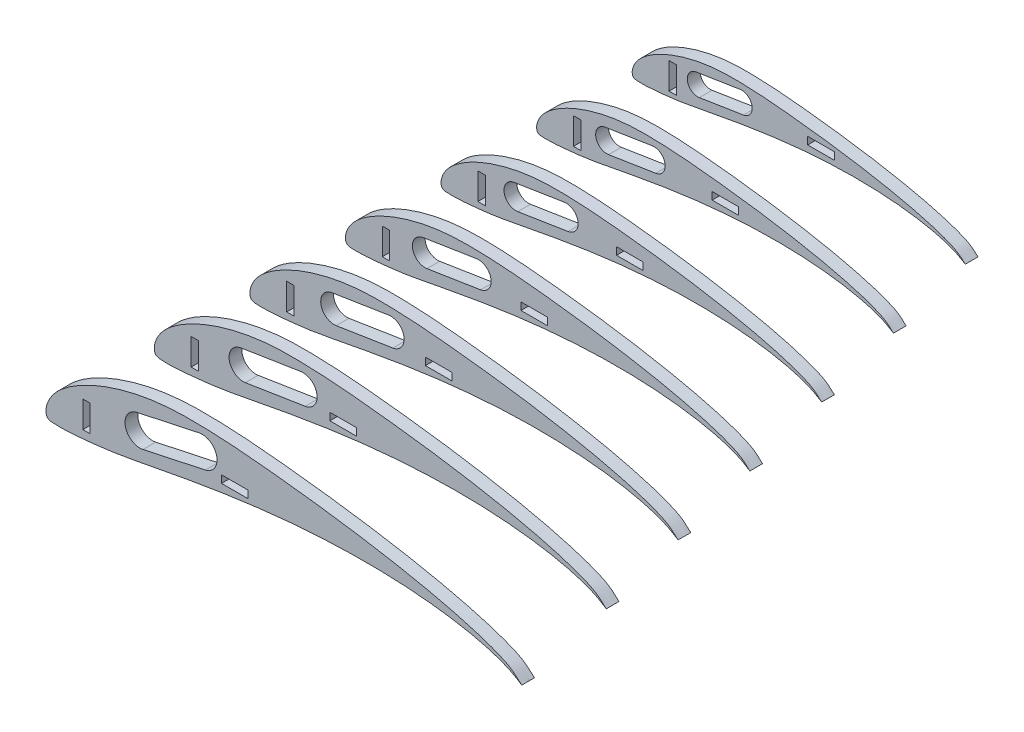
SolidWorks part; units mm, degrees
material "Balsa"
ref_plane "Front Plane" through (0, 0, 0) normal (1, 0, 0) x (0, 1, 0)
ref_plane "Top Plane" through (0, 0, 0) normal (0, 0, 1) x (0, 1, 0)
ref_plane "Right Plane" through (0, 0, 0) normal (0, 1, 0) x (-1, 0, 0)
curve "Curve1"
  spline degree 3 poles (0.9961, 0.0026, 0) (1.0009, -0.0006, 0) (0.9967, 0.0025, 0) (0.9939, 0.0052, 0) (0.9878, 0.0109, 0) (0.9805, 0.017, 0) (0.9705, 0.0231, 0) (0.9581, 0.029, 0) (0.9432, 0.0352, 0) (0.9257, 0.0415, 0) (0.9057, 0.048, 0) (0.8834, 0.0546, 0) (0.8588, 0.0611, 0) (0.8322, 0.0677, 0) (0.8036, 0.0742, 0) (0.7732, 0.0806, 0) (0.7412, 0.0869, 0) (0.7079, 0.0929, 0) (0.6733, 0.0987, 0) (0.6378, 0.1042, 0) (0.6014, 0.1094, 0) (0.5646, 0.1143, 0) (0.5275, 0.1189, 0) (0.4904, 0.1231, 0) (0.4536, 0.1269, 0) (0.4175, 0.1302, 0) (0.3823, 0.1328, 0) (0.3482, 0.1346, 0) (0.3154, 0.1354, 0) (0.284, 0.1353, 0) (0.2541, 0.1338, 0) (0.2258, 0.1307, 0) (0.1988, 0.1263, 0) (0.1732, 0.1206, 0) (0.1489, 0.1139, 0) (0.1262, 0.1063, 0) (0.1051, 0.0981, 0) (0.0858, 0.0892, 0) (0.0682, 0.0798, 0) (0.0525, 0.0701, 0) (0.0388, 0.0602, 0) (0.0271, 0.0502, 0) (0.0176, 0.0401, 0) (0.0103, 0.03, 0) (0.0049, 0.0202, 0) (0.0014, 0.0108, 0) (-0.0002, 0.0022, 0) (0.0001, -0.0051, 0) (0.002, -0.0118, 0) (0.0089, -0.0151, 0) (0.0183, -0.0156, 0) (0.0312, -0.016, 0) (0.0473, -0.0153, 0) (0.0666, -0.0141, 0) (0.0888, -0.012, 0) (0.1137, -0.0092, 0) (0.1411, -0.0057, 0) (0.1711, -0.0007, 0) (0.2038, 0.0055, 0) (0.2393, 0.0123, 0) (0.2775, 0.0195, 0) (0.3182, 0.0267, 0) (0.361, 0.0338, 0) (0.4056, 0.0404, 0) (0.4517, 0.0464, 0) (0.4987, 0.0515, 0) (0.5464, 0.0555, 0) (0.5941, 0.0584, 0) (0.6414, 0.06, 0) (0.6878, 0.0602, 0) (0.7328, 0.059, 0) (0.7758, 0.0564, 0) (0.8164, 0.0525, 0) (0.854, 0.0475, 0) (0.8881, 0.0414, 0) (0.9184, 0.0345, 0) (0.9444, 0.027, 0) (0.9656, 0.0191, 0) (0.9807, 0.0119, 0) (0.9918, 0.0052, 0) (0.9961, 0.0026, 0) (1.0009, -0.0006, 0) (0.9967, 0.0025, 0) knots -0.009748 -0.004147 -0.001 0 0.00098 0.003649 0.007483 0.012095 0.017526 0.024052 0.031783 0.040678 0.05071 0.061833 0.073989 0.087118 0.101145 0.115991 0.13157 0.147788 0.164551 0.181758 0.199312 0.217095 0.23499 0.252857 0.270541 0.287887 0.304773 0.321101 0.336806 0.3518 0.366031 0.379616 0.392653 0.40517 0.417172 0.428604 0.439419 0.449597 0.459102 0.467908 0.475988 0.483309 0.489875 0.495803 0.501149 0.505903 0.510047 0.513579 0.516447 0.51935 0.523823 0.529974 0.537716 0.546968 0.557637 0.56962 0.582804 0.597247 0.613135 0.630444 0.649056 0.668822 0.689595 0.71119 0.733427 0.756094 0.778989 0.80189 0.824567 0.846792 0.868338 0.888978 0.908492 0.926659 0.943286 0.958169 0.971136 0.981956 0.990252 0.995853 0.999 1 1.00098 1.003649 1.007483 periodic
sketch "Sketch2" plane through (0, 0, 0) normal (0, 0, 1) x (0, 1, 0)
  spline S0 degree 3 poles (0.0026, -0.9961) (-0.0006, -1.0009) (0.0025, -0.9967) (0.0052, -0.9939) (0.0109, -0.9878) (0.017, -0.9805) (0.0231, -0.9705) (0.029, -0.9581) (0.0352, -0.9432) (0.0415, -0.9257) (0.048, -0.9057) (0.0546, -0.8834) (0.0611, -0.8588) (0.0677, -0.8322) (0.0742, -0.8036) (0.0806, -0.7732) (0.0869, -0.7412) (0.0929, -0.7079) (0.0987, -0.6733) (0.1042, -0.6378) (0.1094, -0.6014) (0.1143, -0.5646) (0.1189, -0.5275) (0.1231, -0.4904) (0.1269, -0.4536) (0.1302, -0.4175) (0.1328, -0.3823) (0.1346, -0.3482) (0.1354, -0.3154) (0.1353, -0.284) (0.1338, -0.2541) (0.1307, -0.2258) (0.1263, -0.1988) (0.1206, -0.1732) (0.1139, -0.1489) (0.1063, -0.1262) (0.0981, -0.1051) (0.0892, -0.0858) (0.0798, -0.0682) (0.0701, -0.0525) (0.0602, -0.0388) (0.0502, -0.0271) (0.0401, -0.0176) (0.03, -0.0103) (0.0202, -0.0049) (0.0108, -0.0014) (0.0022, 0.0002) (-0.0051, -0.0001) (-0.0118, -0.002) (-0.0151, -0.0089) (-0.0156, -0.0183) (-0.016, -0.0312) (-0.0153, -0.0473) (-0.0141, -0.0666) (-0.012, -0.0888) (-0.0092, -0.1137) (-0.0057, -0.1411) (-0.0007, -0.1711) (0.0055, -0.2038) (0.0123, -0.2393) (0.0195, -0.2775) (0.0267, -0.3182) (0.0338, -0.361) (0.0404, -0.4056) (0.0464, -0.4517) (0.0515, -0.4987) (0.0555, -0.5464) (0.0584, -0.5941) (0.06, -0.6414) (0.0602, -0.6878) (0.059, -0.7328) (0.0564, -0.7758) (0.0525, -0.8164) (0.0475, -0.854) (0.0414, -0.8881) (0.0345, -0.9184) (0.027, -0.9444) (0.0191, -0.9656) (0.0119, -0.9807) (0.0052, -0.9918) (0.0026, -0.9961) (-0.0006, -1.0009) (0.0025, -0.9967) knots -0.009748 -0.004147 -0.001 0 0.00098 0.003649 0.007483 0.012095 0.017526 0.024052 0.031783 0.040678 0.05071 0.061833 0.073989 0.087118 0.101145 0.115991 0.13157 0.147788 0.164551 0.181758 0.199312 0.217095 0.23499 0.252857 0.270541 0.287887 0.304773 0.321101 0.336806 0.3518 0.366031 0.379616 0.392653 0.40517 0.417172 0.428604 0.439419 0.449597 0.459102 0.467908 0.475988 0.483309 0.489875 0.495803 0.501149 0.505903 0.510047 0.513579 0.516447 0.51935 0.523823 0.529974 0.537716 0.546968 0.557637 0.56962 0.582804 0.597247 0.613135 0.630444 0.649056 0.668822 0.689595 0.71119 0.733427 0.756094 0.778989 0.80189 0.824567 0.846792 0.868338 0.888978 0.908492 0.926659 0.943286 0.958169 0.971136 0.981956 0.990252 0.995853 0.999 1 1.00098 1.003649 1.007483 only from (0, -1) to (0, -1) construction
  spline S1 degree 3 poles (0.0026, -0.9961) (-0.0006, -1.0009) (0.0025, -0.9967) (0.0052, -0.9939) (0.0109, -0.9878) (0.017, -0.9805) (0.0231, -0.9705) (0.029, -0.9581) (0.0352, -0.9432) (0.0415, -0.9257) (0.048, -0.9057) (0.0546, -0.8834) (0.0611, -0.8588) (0.0677, -0.8322) (0.0742, -0.8036) (0.0806, -0.7732) (0.0869, -0.7412) (0.0929, -0.7079) (0.0987, -0.6733) (0.1042, -0.6378) (0.1094, -0.6014) (0.1143, -0.5646) (0.1189, -0.5275) (0.1231, -0.4904) (0.1269, -0.4536) (0.1302, -0.4175) (0.1328, -0.3823) (0.1346, -0.3482) (0.1354, -0.3154) (0.1353, -0.284) (0.1338, -0.2541) (0.1307, -0.2258) (0.1263, -0.1988) (0.1206, -0.1732) (0.1139, -0.1489) (0.1063, -0.1262) (0.0981, -0.1051) (0.0892, -0.0858) (0.0798, -0.0682) (0.0701, -0.0525) (0.0602, -0.0388) (0.0502, -0.0271) (0.0401, -0.0176) (0.03, -0.0103) (0.0202, -0.0049) (0.0108, -0.0014) (0.0022, 0.0002) (-0.0051, -0.0001) (-0.0118, -0.002) (-0.0151, -0.0089) (-0.0156, -0.0183) (-0.016, -0.0312) (-0.0153, -0.0473) (-0.0141, -0.0666) (-0.012, -0.0888) (-0.0092, -0.1137) (-0.0057, -0.1411) (-0.0007, -0.1711) (0.0055, -0.2038) (0.0123, -0.2393) (0.0195, -0.2775) (0.0267, -0.3182) (0.0338, -0.361) (0.0404, -0.4056) (0.0464, -0.4517) (0.0515, -0.4987) (0.0555, -0.5464) (0.0584, -0.5941) (0.06, -0.6414) (0.0602, -0.6878) (0.059, -0.7328) (0.0564, -0.7758) (0.0525, -0.8164) (0.0475, -0.854) (0.0414, -0.8881) (0.0345, -0.9184) (0.027, -0.9444) (0.0191, -0.9656) (0.0119, -0.9807) (0.0052, -0.9918) (0.0026, -0.9961) (-0.0006, -1.0009) (0.0025, -0.9967) knots -0.009748 -0.004147 -0.001 0 0.00098 0.003649 0.007483 0.012095 0.017526 0.024052 0.031783 0.040678 0.05071 0.061833 0.073989 0.087118 0.101145 0.115991 0.13157 0.147788 0.164551 0.181758 0.199312 0.217095 0.23499 0.252857 0.270541 0.287887 0.304773 0.321101 0.336806 0.3518 0.366031 0.379616 0.392653 0.40517 0.417172 0.428604 0.439419 0.449597 0.459102 0.467908 0.475988 0.483309 0.489875 0.495803 0.501149 0.505903 0.510047 0.513579 0.516447 0.51935 0.523823 0.529974 0.537716 0.546968 0.557637 0.56962 0.582804 0.597247 0.613135 0.630444 0.649056 0.668822 0.689595 0.71119 0.733427 0.756094 0.778989 0.80189 0.824567 0.846792 0.868338 0.888978 0.908492 0.926659 0.943286 0.958169 0.971136 0.981956 0.990252 0.995853 0.999 1 1.00098 1.003649 1.007483 only from (0, -1) to (0, -1)
  spline S2 degree 3 poles (0.5817, -223.1332) (-0.1446, -224.2031) (0.5543, -223.265) (1.1654, -222.6422) (2.4417, -221.2594) (3.7994, -219.628) (5.1681, -217.3965) (6.4946, -214.6215) (7.8789, -211.2714) (9.3018, -207.3514) (10.7532, -202.8797) (12.2206, -197.8796) (13.697, -192.379) (15.1689, -186.4082) (16.6256, -180.0017) (18.0581, -173.1974) (19.4589, -166.037) (20.8109, -158.5624) (22.1121, -150.8205) (23.3457, -142.856) (24.5142, -134.7205) (25.6083, -126.466) (26.6244, -118.1523) (27.5699, -109.846) (28.4208, -101.6157) (29.1612, -93.5286) (29.7494, -85.6414) (30.154, -77.9993) (30.3288, -70.6447) (30.3102, -63.6154) (29.966, -56.9245) (29.2685, -50.5693) (28.2823, -44.524) (27.0047, -38.7872) (25.5065, -33.3646) (23.8143, -28.2794) (21.9676, -23.553) (19.9763, -19.2149) (17.8809, -15.279) (15.7052, -11.7667) (13.4787, -8.7) (11.2485, -6.0802) (8.9904, -3.9452) (6.7238, -2.3053) (4.5187, -1.094) (2.4251, -0.3176) (0.4927, 0.0523) (-1.1416, -0.0191) (-2.6406, -0.4398) (-3.3847, -2.0039) (-3.4891, -4.1068) (-3.5903, -6.9836) (-3.4343, -10.6014) (-3.1476, -14.9192) (-2.6884, -19.8891) (-2.067, -25.4601) (-1.2702, -31.6052) (-0.1566, -38.3213) (1.2399, -45.641) (2.7597, -53.6011) (4.3644, -62.1626) (5.9874, -71.2717) (7.5678, -80.8615) (9.0528, -90.8576) (10.3879, -101.1739) (11.5342, -111.7177) (12.4404, -122.3892) (13.0827, -133.0814) (13.4358, -143.6827) (13.4805, -154.0779) (13.2135, -164.1512) (12.6412, -173.7872) (11.771, -182.8699) (10.6363, -191.2914) (9.27, -198.9419) (7.7178, -205.7317) (6.0569, -211.5357) (4.2843, -216.2857) (2.6621, -219.6747) (1.1621, -222.1733) (0.5817, -223.1332) (-0.1446, -224.2031) (0.5543, -223.265) knots -0.009748 -0.004147 -0.001 0 0.00098 0.003649 0.007483 0.012095 0.017526 0.024052 0.031783 0.040678 0.05071 0.061833 0.073989 0.087118 0.101145 0.115991 0.13157 0.147788 0.164551 0.181758 0.199312 0.217095 0.23499 0.252857 0.270541 0.287887 0.304773 0.321101 0.336806 0.3518 0.366031 0.379616 0.392653 0.40517 0.417172 0.428604 0.439419 0.449597 0.459102 0.467908 0.475988 0.483309 0.489875 0.495803 0.501149 0.505903 0.510047 0.513579 0.516447 0.51935 0.523823 0.529974 0.537716 0.546968 0.557637 0.56962 0.582804 0.597247 0.613135 0.630444 0.649056 0.668822 0.689595 0.71119 0.733427 0.756094 0.778989 0.80189 0.824567 0.846792 0.868338 0.888978 0.908492 0.926659 0.943286 0.958169 0.971136 0.981956 0.990252 0.995853 0.999 1 1.00098 1.003649 1.007483 only from (0, -224) to (0, -224)
extrude "Boss-Extrude1" add sketch "Sketch2" along normal blind 6 contours S2
sketch "Sketch3" plane through (0, 0, 0) normal (0, 0, -1) x (1, 0, 0)
  line L2 (58.8605, -3.7419) -> (58.8605, -30.0419) construction
  line L7 (44.1949, -13.7419) -> (73.526, -20.0419) construction
  line L8 (45.6649, -6.898) -> (74.996, -13.198)
  line L9 (42.7249, -20.5858) -> (72.056, -26.8858)
  arc A5 (45.6649, -6.898) -> (42.7249, -20.5858) centre (44.1949, -13.7419) ccw
  arc A6 (72.056, -26.8858) -> (74.996, -13.198) centre (73.526, -20.0419) ccw
  spline S0 degree 3 poles (223.265, -0.5543) (224.2031, 0.1446) (223.1332, -0.5817) (222.1733, -1.1621) (219.6747, -2.6621) (216.2857, -4.2843) (211.5357, -6.0569) (205.7317, -7.7178) (198.9419, -9.27) (191.2914, -10.6363) (182.8699, -11.771) (173.7872, -12.6412) (164.1512, -13.2135) (154.0779, -13.4805) (143.6827, -13.4358) (133.0814, -13.0827) (122.3892, -12.4404) (111.7177, -11.5342) (101.1739, -10.3879) (90.8576, -9.0528) (80.8615, -7.5678) (71.2717, -5.9874) (62.1626, -4.3644) (53.6011, -2.7597) (45.641, -1.2399) (38.3213, 0.1566) (31.6052, 1.2702) (25.4601, 2.067) (19.8891, 2.6884) (14.9192, 3.1476) (10.6014, 3.4343) (6.9836, 3.5903) (4.1068, 3.4891) (2.0039, 3.3847) (0.4398, 2.6406) (0.0191, 1.1416) (-0.0523, -0.4927) (0.3176, -2.4251) (1.094, -4.5187) (2.3053, -6.7238) (3.9452, -8.9904) (6.0802, -11.2485) (8.7, -13.4787) (11.7667, -15.7052) (15.279, -17.8809) (19.2149, -19.9763) (23.553, -21.9676) (28.2794, -23.8143) (33.3646, -25.5065) (38.7872, -27.0047) (44.524, -28.2823) (50.5693, -29.2685) (56.9245, -29.966) (63.6154, -30.3102) (70.6447, -30.3288) (77.9993, -30.154) (85.6414, -29.7494) (93.5286, -29.1612) (101.6157, -28.4208) (109.846, -27.5699) (118.1523, -26.6244) (126.466, -25.6083) (134.7205, -24.5142) (142.856, -23.3457) (150.8205, -22.1121) (158.5624, -20.8109) (166.037, -19.4589) (173.1974, -18.0581) (180.0017, -16.6256) (186.4082, -15.1689) (192.379, -13.697) (197.8796, -12.2206) (202.8797, -10.7532) (207.3514, -9.3018) (211.2714, -7.8789) (214.6215, -6.4946) (217.3965, -5.1681) (219.628, -3.7994) (221.2594, -2.4417) (222.6422, -1.1654) (223.265, -0.5543) (224.2031, 0.1446) (223.1332, -0.5817) knots -0.007483 -0.003649 -0.00098 0 0.001 0.004147 0.009748 0.018044 0.028864 0.041831 0.056714 0.073341 0.091508 0.111022 0.131662 0.153208 0.175433 0.19811 0.221011 0.243906 0.266573 0.28881 0.310405 0.331178 0.350944 0.369556 0.386865 0.402753 0.417196 0.43038 0.442363 0.453032 0.462284 0.470026 0.476177 0.48065 0.483553 0.486421 0.489953 0.494097 0.498851 0.504197 0.510125 0.516691 0.524012 0.532092 0.540898 0.550403 0.560581 0.571396 0.582828 0.59483 0.607347 0.620384 0.633969 0.6482 0.663194 0.678899 0.695227 0.712113 0.729459 0.747143 0.76501 0.782905 0.800688 0.818242 0.835449 0.852212 0.86843 0.884009 0.898855 0.912882 0.926011 0.938167 0.94929 0.959322 0.968217 0.975948 0.982474 0.987905 0.992517 0.996351 0.99902 1 1.001 1.004147 1.009748 only from (224, 0) to (224, 0) construction
  point P9 (0, 0)
  point P10 (0, 0)
  point P22 (58.8605, -16.8919)
  dimension "D1" = 10
  dimension "D3" = 30
  dimension "D9" = 7
  dimension "D4" = 26.3
extrude "Cut-Extrude1" cut sketch "Sketch3" against normal blind 10
sketch "Sketch4" plane through (0, 0, 0) normal (0, 0, -1) x (-1, 0, 0)
  point P0 (0, 0)
ref_plane "Plane1" through (-0.0039, 0, 0) normal (-0.9999, 0.0105, 0) x (0, 0, 1)
ref_plane "Plane2" through (0, 0, -45) normal (0, 0, -1) x (-1, 0, 0)
ref_plane "Plane3" through (0, 0, -90) normal (0, 0, -1) x (-1, 0, 0)
ref_plane "Plane4" through (0, 0, -135) normal (0, 0, -1) x (-1, 0, 0)
ref_plane "Plane5" through (0, 0, -180) normal (0, 0, -1) x (-1, 0, 0)
ref_plane "Plane6" through (0, 0, -225) normal (0, 0, -1) x (-1, 0, 0)
ref_plane "Plane7" through (0, 0, -270) normal (0, 0, -1) x (-1, 0, 0)
sketch "Sketch5" plane through (0, 0, -45) normal (0, 0, -1) x (-1, 0, 0)
  line L4 (-40.8046, 20.3934) -> (-68.9559, 24.8385)
  line L5 (-71.0302, 11.7013) -> (-42.879, 7.2561)
  arc A4 (-42.879, 7.2561) -> (-40.8046, 20.3934) centre (-41.8418, 13.8248) ccw
  arc A5 (-68.9559, 24.8385) -> (-71.0302, 11.7013) centre (-69.993, 18.2699) ccw
  spline S2 degree 3 poles (-212.1017, 0.5266) (-212.9929, -0.1374) (-211.9765, 0.5526) (-211.0646, 1.104) (-208.691, 2.529) (-205.4714, 4.0701) (-200.9589, 5.7541) (-195.4451, 7.3319) (-188.9948, 8.8065) (-181.7268, 10.1045) (-173.7264, 11.1825) (-165.0978, 12.0092) (-155.9436, 12.5528) (-146.374, 12.8064) (-136.4985, 12.7641) (-126.4274, 12.4286) (-116.2697, 11.8183) (-106.1318, 10.9575) (-96.1152, 9.8685) (-86.3147, 8.6001) (-76.8184, 7.1894) (-67.7081, 5.688) (-59.0545, 4.1462) (-50.9211, 2.6217) (-43.359, 1.1779) (-36.4052, -0.1488) (-30.0249, -1.2067) (-24.1871, -1.9637) (-18.8946, -2.554) (-14.1732, -2.9902) (-10.0713, -3.2626) (-6.6344, -3.4108) (-3.9015, -3.3146) (-1.9037, -3.2155) (-0.4179, -2.5086) (-0.0181, -1.0846) (0.0497, 0.4681) (-0.3017, 2.3039) (-1.0393, 4.2928) (-2.19, 6.3876) (-3.748, 8.5408) (-5.7762, 10.6861) (-8.265, 12.8047) (-11.1783, 14.9199) (-14.5151, 16.9869) (-18.2542, 18.9775) (-22.3754, 20.8692) (-26.8654, 22.6236) (-31.6964, 24.2312) (-36.8478, 25.6545) (-42.2978, 26.8682) (-48.0408, 27.8051) (-54.0783, 28.4677) (-60.4347, 28.7947) (-67.1125, 28.8123) (-74.0993, 28.6463) (-81.3593, 28.2619) (-88.8521, 27.7031) (-96.5349, 26.9997) (-104.3537, 26.1914) (-112.2447, 25.2932) (-120.1427, 24.3278) (-127.9845, 23.2885) (-135.7132, 22.1784) (-143.2795, 21.0065) (-150.6342, 19.7704) (-157.7352, 18.486) (-164.5375, 17.1552) (-171.0016, 15.7943) (-177.0878, 14.4104) (-182.76, 13.0121) (-187.9856, 11.6095) (-192.7358, 10.2156) (-196.9839, 8.8367) (-200.7079, 7.4849) (-203.8904, 6.1698) (-206.5267, 4.9097) (-208.6466, 3.6094) (-210.1964, 2.3196) (-211.5101, 1.1071) (-212.1017, 0.5266) (-212.9929, -0.1374) (-211.9765, 0.5526) knots -0.007483 -0.003649 -0.00098 0 0.001 0.004147 0.009748 0.018044 0.028864 0.041831 0.056714 0.073341 0.091508 0.111022 0.131662 0.153208 0.175433 0.19811 0.221011 0.243906 0.266573 0.28881 0.310405 0.331178 0.350944 0.369556 0.386865 0.402753 0.417196 0.43038 0.442363 0.453032 0.462284 0.470026 0.476177 0.48065 0.483553 0.486421 0.489953 0.494097 0.498851 0.504197 0.510125 0.516691 0.524012 0.532092 0.540898 0.550403 0.560581 0.571396 0.582828 0.59483 0.607347 0.620384 0.633969 0.6482 0.663194 0.678899 0.695227 0.712113 0.729459 0.747143 0.76501 0.782905 0.800688 0.818242 0.835449 0.852212 0.86843 0.884009 0.898855 0.912882 0.926011 0.938167 0.94929 0.959322 0.968217 0.975948 0.982474 0.987905 0.992517 0.996351 0.99902 1 1.001 1.004147 1.009748 only from (-212.8, 0) to (-212.8, 0)
sketch "Sketch6" plane through (0, 0, -90) normal (0, 0, -1) x (-1, 0, 0)
  line L4 (-38.657, 19.32) -> (-65.3266, 23.5312)
  line L5 (-67.2918, 11.0854) -> (-40.6222, 6.8742)
  arc A4 (-40.6222, 6.8742) -> (-38.657, 19.32) centre (-39.6396, 13.0971) ccw
  arc A5 (-65.3266, 23.5312) -> (-67.2918, 11.0854) centre (-66.3092, 17.3083) ccw
  spline S2 degree 3 poles (-200.9385, 0.4989) (-201.7828, -0.1301) (-200.8198, 0.5235) (-199.956, 1.0459) (-197.7072, 2.3959) (-194.6571, 3.8559) (-190.3821, 5.4512) (-185.1585, 6.946) (-179.0477, 8.343) (-172.1623, 9.5727) (-164.5829, 10.5939) (-156.4085, 11.3771) (-147.7361, 11.8921) (-138.6701, 12.1324) (-129.3144, 12.0923) (-119.7733, 11.7744) (-110.1503, 11.1963) (-100.5459, 10.3808) (-91.0565, 9.3491) (-81.7719, 8.1475) (-72.7753, 6.811) (-64.1445, 5.3887) (-55.9463, 3.928) (-48.241, 2.4837) (-41.0769, 1.1159) (-34.4891, -0.1409) (-28.4447, -1.1432) (-22.9141, -1.8603) (-17.9002, -2.4195) (-13.4273, -2.8328) (-9.5412, -3.0908) (-6.2853, -3.2313) (-3.6961, -3.1402) (-1.8035, -3.0462) (-0.3959, -2.3766) (-0.0172, -1.0275) (0.0471, 0.4434) (-0.2858, 2.1826) (-0.9846, 4.0668) (-2.0748, 6.0514) (-3.5507, 8.0913) (-5.4721, 10.1237) (-7.83, 12.1308) (-10.59, 14.1347) (-13.7511, 16.0928) (-17.2934, 17.9787) (-21.1977, 19.7708) (-25.4514, 21.4328) (-30.0282, 22.9559) (-34.9084, 24.3042) (-40.0716, 25.4541) (-45.5124, 26.3417) (-51.232, 26.9694) (-57.2539, 27.2792) (-63.5803, 27.2959) (-70.1994, 27.1386) (-77.0773, 26.7745) (-84.1757, 26.2451) (-91.4542, 25.5787) (-98.8614, 24.8129) (-106.3371, 23.962) (-113.8194, 23.0474) (-121.2484, 22.0628) (-128.5704, 21.0111) (-135.7384, 19.9009) (-142.7061, 18.7298) (-149.4333, 17.513) (-155.8777, 16.2523) (-162.0015, 14.9631) (-167.7674, 13.652) (-173.1411, 12.3273) (-178.0916, 10.9985) (-182.5918, 9.6779) (-186.6163, 8.3716) (-190.1443, 7.091) (-193.1593, 5.8451) (-195.6568, 4.6513) (-197.6652, 3.4194) (-199.1335, 2.1975) (-200.378, 1.0488) (-200.9385, 0.4989) (-201.7828, -0.1301) (-200.8198, 0.5235) knots -0.007483 -0.003649 -0.00098 0 0.001 0.004147 0.009748 0.018044 0.028864 0.041831 0.056714 0.073341 0.091508 0.111022 0.131662 0.153208 0.175433 0.19811 0.221011 0.243906 0.266573 0.28881 0.310405 0.331178 0.350944 0.369556 0.386865 0.402753 0.417196 0.43038 0.442363 0.453032 0.462284 0.470026 0.476177 0.48065 0.483553 0.486421 0.489953 0.494097 0.498851 0.504197 0.510125 0.516691 0.524012 0.532092 0.540898 0.550403 0.560581 0.571396 0.582828 0.59483 0.607347 0.620384 0.633969 0.6482 0.663194 0.678899 0.695227 0.712113 0.729459 0.747143 0.76501 0.782905 0.800688 0.818242 0.835449 0.852212 0.86843 0.884009 0.898855 0.912882 0.926011 0.938167 0.94929 0.959322 0.968217 0.975948 0.982474 0.987905 0.992517 0.996351 0.99902 1 1.001 1.004147 1.009748 only from (-201.6, 0) to (-201.6, 0)
sketch "Sketch7" plane through (0, 0, -135) normal (0, 0, -1) x (-1, 0, 0)
  line L4 (-36.5094, 18.2467) -> (-61.6973, 22.2239)
  line L5 (-63.5534, 10.4696) -> (-38.3654, 6.4923)
  arc A4 (-38.3654, 6.4923) -> (-36.5094, 18.2467) centre (-37.4374, 12.3695) ccw
  arc A5 (-61.6973, 22.2239) -> (-63.5534, 10.4696) centre (-62.6254, 16.3467) ccw
  spline S2 degree 3 poles (-189.7752, 0.4712) (-190.5726, -0.1229) (-189.6632, 0.4944) (-188.8473, 0.9878) (-186.7235, 2.2628) (-183.8428, 3.6416) (-179.8053, 5.1484) (-174.8719, 6.5601) (-169.1006, 7.8795) (-162.5977, 9.0409) (-155.4395, 10.0054) (-147.7191, 10.745) (-139.5285, 11.2315) (-130.9662, 11.4584) (-122.1303, 11.4205) (-113.1192, 11.1203) (-104.0308, 10.5743) (-94.96, 9.8041) (-85.9979, 8.8297) (-77.229, 7.6948) (-68.7323, 6.4326) (-60.5809, 5.0893) (-52.8382, 3.7097) (-45.5609, 2.3457) (-38.7949, 1.0539) (-32.5731, -0.1331) (-26.8644, -1.0797) (-21.6411, -1.757) (-16.9057, -2.2851) (-12.6813, -2.6754) (-9.0112, -2.9191) (-5.9361, -3.0517) (-3.4908, -2.9657) (-1.7033, -2.877) (-0.3739, -2.2445) (-0.0162, -0.9704) (0.0445, 0.4188) (-0.27, 2.0613) (-0.9299, 3.8409) (-1.9595, 5.7152) (-3.3534, 7.6418) (-5.1681, 9.5612) (-7.395, 11.4569) (-10.0017, 13.3494) (-12.9872, 15.1988) (-16.3327, 16.9799) (-20.0201, 18.6724) (-24.0375, 20.2421) (-28.3599, 21.6805) (-32.9691, 22.954) (-37.8454, 24.04) (-42.9839, 24.8783) (-48.3858, 25.4711) (-54.0731, 25.7637) (-60.048, 25.7795) (-66.2994, 25.6309) (-72.7952, 25.287) (-79.4993, 24.787) (-86.3734, 24.1577) (-93.3691, 23.4344) (-100.4295, 22.6308) (-107.4961, 21.767) (-114.5124, 20.8371) (-121.4276, 19.8439) (-128.1974, 18.7953) (-134.778, 17.6893) (-141.1315, 16.5401) (-147.2178, 15.3494) (-153.0014, 14.1318) (-158.447, 12.8936) (-163.5221, 11.6424) (-168.1976, 10.3875) (-172.4478, 9.1402) (-176.2487, 7.9065) (-179.5807, 6.697) (-182.4283, 5.5204) (-184.787, 4.3929) (-186.6838, 3.2295) (-188.0705, 2.0754) (-189.2459, 0.9906) (-189.7752, 0.4712) (-190.5726, -0.1229) (-189.6632, 0.4944) knots -0.007483 -0.003649 -0.00098 0 0.001 0.004147 0.009748 0.018044 0.028864 0.041831 0.056714 0.073341 0.091508 0.111022 0.131662 0.153208 0.175433 0.19811 0.221011 0.243906 0.266573 0.28881 0.310405 0.331178 0.350944 0.369556 0.386865 0.402753 0.417196 0.43038 0.442363 0.453032 0.462284 0.470026 0.476177 0.48065 0.483553 0.486421 0.489953 0.494097 0.498851 0.504197 0.510125 0.516691 0.524012 0.532092 0.540898 0.550403 0.560581 0.571396 0.582828 0.59483 0.607347 0.620384 0.633969 0.6482 0.663194 0.678899 0.695227 0.712113 0.729459 0.747143 0.76501 0.782905 0.800688 0.818242 0.835449 0.852212 0.86843 0.884009 0.898855 0.912882 0.926011 0.938167 0.94929 0.959322 0.968217 0.975948 0.982474 0.987905 0.992517 0.996351 0.99902 1 1.001 1.004147 1.009748 only from (-190.4, 0) to (-190.4, 0)
sketch "Sketch8" plane through (0, 0, -180) normal (0, 0, -1) x (-1, 0, 0)
  line L4 (-34.3618, 17.1734) -> (-58.0681, 20.9166)
  line L5 (-59.8149, 9.8537) -> (-36.1087, 6.1104)
  arc A4 (-36.1087, 6.1104) -> (-34.3618, 17.1734) centre (-35.2352, 11.6419) ccw
  arc A5 (-58.0681, 20.9166) -> (-59.8149, 9.8537) centre (-58.9415, 15.3852) ccw
  spline S2 degree 3 poles (-178.612, 0.4435) (-179.3625, -0.1157) (-178.5065, 0.4654) (-177.7386, 0.9297) (-175.7397, 2.1297) (-173.0286, 3.4274) (-169.2286, 4.8455) (-164.5854, 6.1742) (-159.1535, 7.416) (-153.0331, 8.509) (-146.296, 9.4168) (-139.0297, 10.113) (-131.321, 10.5708) (-123.2623, 10.7844) (-114.9461, 10.7487) (-106.4651, 10.4662) (-97.9114, 9.9523) (-89.3741, 9.2274) (-80.9392, 8.3103) (-72.6861, 7.2422) (-64.6892, 6.0542) (-57.0173, 4.7899) (-49.7301, 3.4915) (-42.8809, 2.2078) (-36.5128, 0.9919) (-30.657, -0.1253) (-25.2841, -1.0162) (-20.3681, -1.6536) (-15.9113, -2.1507) (-11.9354, -2.5181) (-8.4811, -2.7474) (-5.5869, -2.8722) (-3.2855, -2.7913) (-1.6031, -2.7078) (-0.3519, -2.1125) (-0.0153, -0.9133) (0.0419, 0.3942) (-0.2541, 1.9401) (-0.8752, 3.615) (-1.8442, 5.379) (-3.1562, 7.1923) (-4.8641, 8.9988) (-6.96, 10.7829) (-9.4133, 12.5642) (-12.2232, 14.3047) (-15.3719, 15.9811) (-18.8424, 17.5741) (-22.6235, 19.0514) (-26.6917, 20.4052) (-31.0297, 21.6038) (-35.6192, 22.6259) (-40.4554, 23.4148) (-45.5396, 23.9728) (-50.8924, 24.2481) (-56.5158, 24.263) (-62.3994, 24.1232) (-68.5131, 23.7995) (-74.8229, 23.3289) (-81.2926, 22.7366) (-87.8768, 22.0559) (-94.5219, 21.2995) (-101.1728, 20.4866) (-107.7764, 19.6114) (-114.2848, 18.6766) (-120.6564, 17.6897) (-126.8499, 16.6487) (-132.8296, 15.5672) (-138.5579, 14.4465) (-144.0013, 13.3005) (-149.1266, 12.1351) (-153.9032, 10.9576) (-158.3037, 9.7765) (-162.3038, 8.6026) (-165.8811, 7.4414) (-169.0172, 6.3031) (-171.6972, 5.1957) (-173.9172, 4.1345) (-175.7024, 3.0395) (-177.0075, 1.9533) (-178.1138, 0.9323) (-178.612, 0.4435) (-179.3625, -0.1157) (-178.5065, 0.4654) knots -0.007483 -0.003649 -0.00098 0 0.001 0.004147 0.009748 0.018044 0.028864 0.041831 0.056714 0.073341 0.091508 0.111022 0.131662 0.153208 0.175433 0.19811 0.221011 0.243906 0.266573 0.28881 0.310405 0.331178 0.350944 0.369556 0.386865 0.402753 0.417196 0.43038 0.442363 0.453032 0.462284 0.470026 0.476177 0.48065 0.483553 0.486421 0.489953 0.494097 0.498851 0.504197 0.510125 0.516691 0.524012 0.532092 0.540898 0.550403 0.560581 0.571396 0.582828 0.59483 0.607347 0.620384 0.633969 0.6482 0.663194 0.678899 0.695227 0.712113 0.729459 0.747143 0.76501 0.782905 0.800688 0.818242 0.835449 0.852212 0.86843 0.884009 0.898855 0.912882 0.926011 0.938167 0.94929 0.959322 0.968217 0.975948 0.982474 0.987905 0.992517 0.996351 0.99902 1 1.001 1.004147 1.009748 only from (-179.2, 0) to (-179.2, 0)
sketch "Sketch9" plane through (0, 0, -225) normal (0, 0, -1) x (-1, 0, 0)
  line L4 (-32.2142, 16.1) -> (-54.4388, 19.6093)
  line L5 (-56.0765, 9.2378) -> (-33.8519, 5.7285)
  arc A4 (-33.8519, 5.7285) -> (-32.2142, 16.1) centre (-33.033, 10.9143) ccw
  arc A5 (-54.4388, 19.6093) -> (-56.0765, 9.2378) centre (-55.2577, 14.4236) ccw
  spline S2 degree 3 poles (-167.4487, 0.4158) (-168.1523, -0.1084) (-167.3499, 0.4363) (-166.63, 0.8716) (-164.756, 1.9966) (-162.2143, 3.2132) (-158.6518, 4.5427) (-154.2988, 5.7884) (-149.2064, 6.9525) (-143.4685, 7.9772) (-137.1525, 8.8283) (-130.3404, 9.4809) (-123.1134, 9.9101) (-115.5584, 10.1103) (-107.762, 10.0769) (-99.8111, 9.812) (-91.7919, 9.3303) (-83.7882, 8.6507) (-75.8805, 7.7909) (-68.1432, 6.7896) (-60.6461, 5.6758) (-53.4538, 4.4906) (-46.6219, 3.2733) (-40.2008, 2.0698) (-34.2308, 0.9299) (-28.7409, -0.1175) (-23.7039, -0.9527) (-19.0951, -1.5503) (-14.9168, -2.0163) (-11.1894, -2.3607) (-7.951, -2.5757) (-5.2377, -2.6927) (-3.0801, -2.6168) (-1.5029, -2.5385) (-0.3299, -1.9805) (-0.0143, -0.8562) (0.0392, 0.3695) (-0.2382, 1.8188) (-0.8205, 3.389) (-1.729, 5.0428) (-2.9589, 6.7428) (-4.5601, 8.4364) (-6.525, 10.109) (-8.825, 11.7789) (-11.4593, 13.4107) (-14.4112, 14.9822) (-17.6648, 16.4757) (-21.2095, 17.8607) (-25.0235, 19.1299) (-29.0904, 20.2535) (-33.393, 21.2118) (-37.927, 21.9514) (-42.6934, 22.4745) (-47.7116, 22.7326) (-52.9836, 22.7466) (-58.4995, 22.6155) (-64.2311, 22.3121) (-70.1464, 21.8709) (-76.2118, 21.3156) (-82.3845, 20.6774) (-88.6143, 19.9683) (-94.8495, 19.2062) (-101.0404, 18.3856) (-107.142, 17.5093) (-113.1154, 16.5841) (-118.9218, 15.6082) (-124.5278, 14.5942) (-129.898, 13.5436) (-135.0012, 12.4692) (-139.8062, 11.3767) (-144.2842, 10.2727) (-148.4097, 9.1654) (-152.1598, 8.0649) (-155.5136, 6.9763) (-158.4536, 5.9092) (-160.9661, 4.8709) (-163.0474, 3.8761) (-164.721, 2.8495) (-165.9446, 1.8312) (-166.9817, 0.874) (-167.4487, 0.4158) (-168.1523, -0.1084) (-167.3499, 0.4363) knots -0.007483 -0.003649 -0.00098 0 0.001 0.004147 0.009748 0.018044 0.028864 0.041831 0.056714 0.073341 0.091508 0.111022 0.131662 0.153208 0.175433 0.19811 0.221011 0.243906 0.266573 0.28881 0.310405 0.331178 0.350944 0.369556 0.386865 0.402753 0.417196 0.43038 0.442363 0.453032 0.462284 0.470026 0.476177 0.48065 0.483553 0.486421 0.489953 0.494097 0.498851 0.504197 0.510125 0.516691 0.524012 0.532092 0.540898 0.550403 0.560581 0.571396 0.582828 0.59483 0.607347 0.620384 0.633969 0.6482 0.663194 0.678899 0.695227 0.712113 0.729459 0.747143 0.76501 0.782905 0.800688 0.818242 0.835449 0.852212 0.86843 0.884009 0.898855 0.912882 0.926011 0.938167 0.94929 0.959322 0.968217 0.975948 0.982474 0.987905 0.992517 0.996351 0.99902 1 1.001 1.004147 1.009748 only from (-168, 0) to (-168, 0)
sketch "Sketch10" plane through (0, 0, -270) normal (0, 0, -1) x (-1, 0, 0)
  line L4 (-30.0666, 15.0267) -> (-50.8096, 18.3021)
  line L5 (-52.3381, 8.622) -> (-31.5951, 5.3466)
  arc A4 (-31.5951, 5.3466) -> (-30.0666, 15.0267) centre (-30.8308, 10.1867) ccw
  arc A5 (-50.8096, 18.3021) -> (-52.3381, 8.622) centre (-51.5738, 13.462) ccw
  spline S2 degree 3 poles (-156.2855, 0.388) (-156.9421, -0.1012) (-156.1932, 0.4072) (-155.5213, 0.8135) (-153.7723, 1.8635) (-151.4, 2.999) (-148.075, 4.2398) (-144.0122, 5.4025) (-139.2593, 6.489) (-133.904, 7.4454) (-128.009, 8.2397) (-121.651, 8.8489) (-114.9058, 9.2494) (-107.8545, 9.4363) (-100.5779, 9.4051) (-93.157, 9.1579) (-85.6724, 8.7083) (-78.2024, 8.074) (-70.8218, 7.2715) (-63.6003, 6.3369) (-56.603, 5.2974) (-49.8902, 4.1912) (-43.5138, 3.0551) (-37.5208, 1.9318) (-31.9487, 0.8679) (-26.8249, -0.1096) (-22.1236, -0.8892) (-17.8221, -1.4469) (-13.9224, -1.8819) (-10.4434, -2.2033) (-7.421, -2.404) (-4.8885, -2.5132) (-2.8748, -2.4424) (-1.4027, -2.3693) (-0.3079, -1.8484) (-0.0134, -0.7992) (0.0366, 0.3449) (-0.2223, 1.6976) (-0.7658, 3.1631) (-1.6137, 4.7066) (-2.7617, 6.2932) (-4.2561, 7.874) (-6.09, 9.4351) (-8.2367, 10.9936) (-10.6953, 12.5166) (-13.4504, 13.9834) (-16.4871, 15.3773) (-19.7956, 16.67) (-23.3552, 17.8546) (-27.151, 18.9033) (-31.1668, 19.7976) (-35.3985, 20.488) (-39.8471, 20.9762) (-44.5308, 21.2171) (-49.4513, 21.2301) (-54.5995, 21.1078) (-59.949, 20.8246) (-65.47, 20.4128) (-71.131, 19.8945) (-76.8922, 19.2989) (-82.7066, 18.6371) (-88.5262, 17.9258) (-94.3043, 17.1599) (-99.9992, 16.342) (-105.5743, 15.4785) (-110.9936, 14.5676) (-116.2259, 13.6213) (-121.2382, 12.6407) (-126.0012, 11.6379) (-130.4858, 10.6182) (-134.6653, 9.5879) (-138.5157, 8.5544) (-142.0158, 7.5272) (-145.146, 6.5112) (-147.89, 5.5152) (-150.235, 4.5462) (-152.1775, 3.6177) (-153.7396, 2.6596) (-154.8816, 1.7092) (-155.8495, 0.8158) (-156.2855, 0.388) (-156.9421, -0.1012) (-156.1932, 0.4072) knots -0.007483 -0.003649 -0.00098 0 0.001 0.004147 0.009748 0.018044 0.028864 0.041831 0.056714 0.073341 0.091508 0.111022 0.131662 0.153208 0.175433 0.19811 0.221011 0.243906 0.266573 0.28881 0.310405 0.331178 0.350944 0.369556 0.386865 0.402753 0.417196 0.43038 0.442363 0.453032 0.462284 0.470026 0.476177 0.48065 0.483553 0.486421 0.489953 0.494097 0.498851 0.504197 0.510125 0.516691 0.524012 0.532092 0.540898 0.550403 0.560581 0.571396 0.582828 0.59483 0.607347 0.620384 0.633969 0.6482 0.663194 0.678899 0.695227 0.712113 0.729459 0.747143 0.76501 0.782905 0.800688 0.818242 0.835449 0.852212 0.86843 0.884009 0.898855 0.912882 0.926011 0.938167 0.94929 0.959322 0.968217 0.975948 0.982474 0.987905 0.992517 0.996351 0.99902 1 1.001 1.004147 1.009748 only from (-156.8, 0) to (-156.8, 0)
extrude "Boss-Extrude8" add sketch "Sketch5" along normal blind 6 separate body
extrude "Boss-Extrude9" add sketch "Sketch6" along normal blind 6 separate body
extrude "Boss-Extrude10" add sketch "Sketch7" along normal blind 6 separate body
extrude "Boss-Extrude11" add sketch "Sketch8" along normal blind 6 separate body
extrude "Boss-Extrude12" add sketch "Sketch9" along normal blind 6 separate body
extrude "Boss-Extrude13" add sketch "Sketch10" along normal blind 6 separate body
sketch "Sketch11" plane through (0, 0, 6) normal (0, 0, 1) x (1, 0, 0)
  line L1 (20.8281, 13.3439) -> (17.3281, 13.3439)
  line L2 (20.8281, 13.3439) -> (20.8281, 0.8439)
  line L3 (20.8281, 0.8439) -> (17.3281, 0.8439)
  line L4 (17.3281, 13.3439) -> (17.3281, 0.8439)
  line L5 (20.8281, 13.3439) -> (17.3281, 0.8439) construction
  line L6 (20.8281, 0.8439) -> (17.3281, 13.3439) construction
  line L7 (95.1354, 15.0727) -> (82.6354, 15.0727)
  line L8 (95.1354, 15.0727) -> (95.1354, 11.5727)
  line L9 (95.1354, 11.5727) -> (82.6354, 11.5727)
  line L10 (82.6354, 15.0727) -> (82.6354, 11.5727)
  line L11 (95.1354, 15.0727) -> (82.6354, 11.5727) construction
  line L12 (95.1354, 11.5727) -> (82.6354, 15.0727) construction
  point P1 (19.0781, 7.0939)
  point P7 (88.8854, 13.3227)
extrude "Cut-Extrude2" cut sketch "Sketch11" against normal through all contours L2 L1 L4 L3 | L8 L7 L10 L9
ref_plane "Plane12" through (0, 0, 16) normal (0, 0, 1) x (1, 0, 0)
